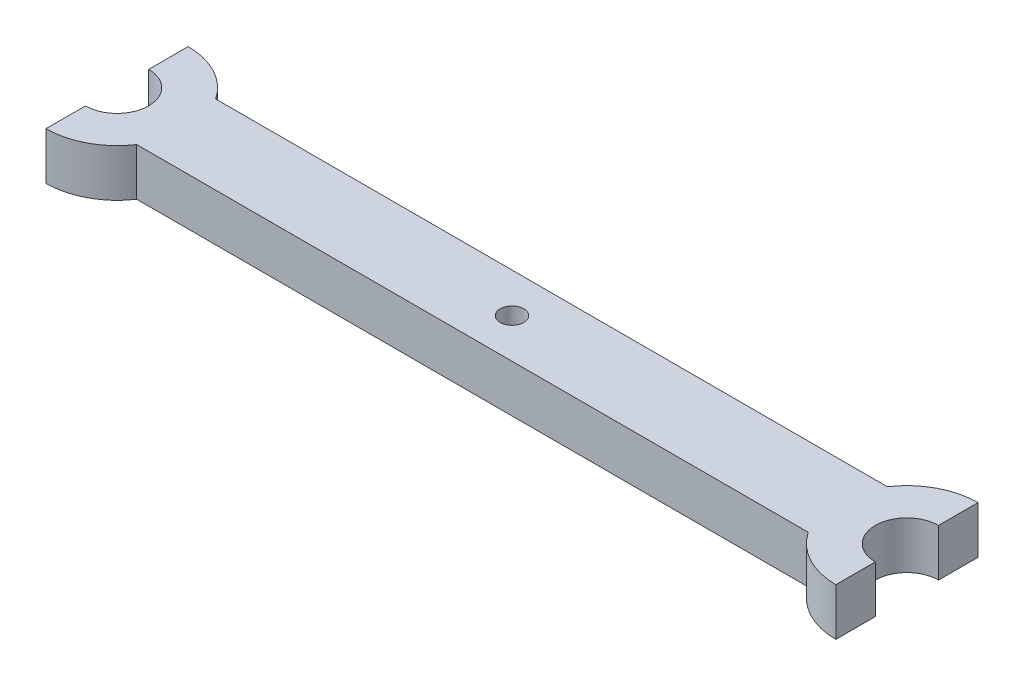
SolidWorks part; units mm, degrees
ref_plane "Front Plane" through (0, 0, 0) normal (0, 0, 1) x (1, 0, 0)
ref_plane "Top Plane" through (0, 0, 0) normal (0, 1, 0) x (1, 0, 0)
ref_plane "Right Plane" through (0, 0, 0) normal (1, 0, 0) x (0, 0, -1)
sketch "Sketch1" plane through (0, 0, 0) normal (0, 1, 0) x (1, 0, 0)
  line L0 (-50, 4) -> (-50, 9)
  line L1 (-50, -4) -> (-50, -9)
  line L2 (-42.5167, -5) -> (42.5167, -5)
  line L3 (-42.5167, 5) -> (42.5167, 5)
  line L4 (50, 4) -> (50, 9)
  line L5 (50, -4) -> (50, -9)
  line L6 (-3.3, 0) -> (3.3, 0) construction
  line L7 (0, -3.3) -> (0, 3.3) construction
  arc A0 (-50, -4) -> (-50, 4) centre (-50, 0) ccw
  arc A1 (-50, 9) -> (-42.5167, 5) centre (-50, 0) cw
  arc A2 (-50, -9) -> (-42.5167, -5) centre (-50, 0) ccw
  arc A3 (50, 4) -> (50, -4) centre (50, 0) ccw
  arc A4 (50, 9) -> (42.5167, 5) centre (50, 0) ccw
  arc A5 (50, -9) -> (42.5167, -5) centre (50, 0) cw
  dimension "D1" = 4
  dimension "D2" = 5
  dimension "D3" = 4
  dimension "D4" = 5
  dimension "D7" = 50
  dimension "D5" = 5
  dimension "D6" = 5
  dimension "D8" = 50
extrude "Boss-Extrude1" add sketch "Sketch1" along normal blind 6
sketch "Sketch2" plane through (0, 6, 0) normal (0, 1, 0) x (1, 0, 0)
  circle A0 centre (0, 0) radius 1.5
  dimension "D1" = 3
extrude "Cut-Extrude1" cut sketch "Sketch2" against normal through all
